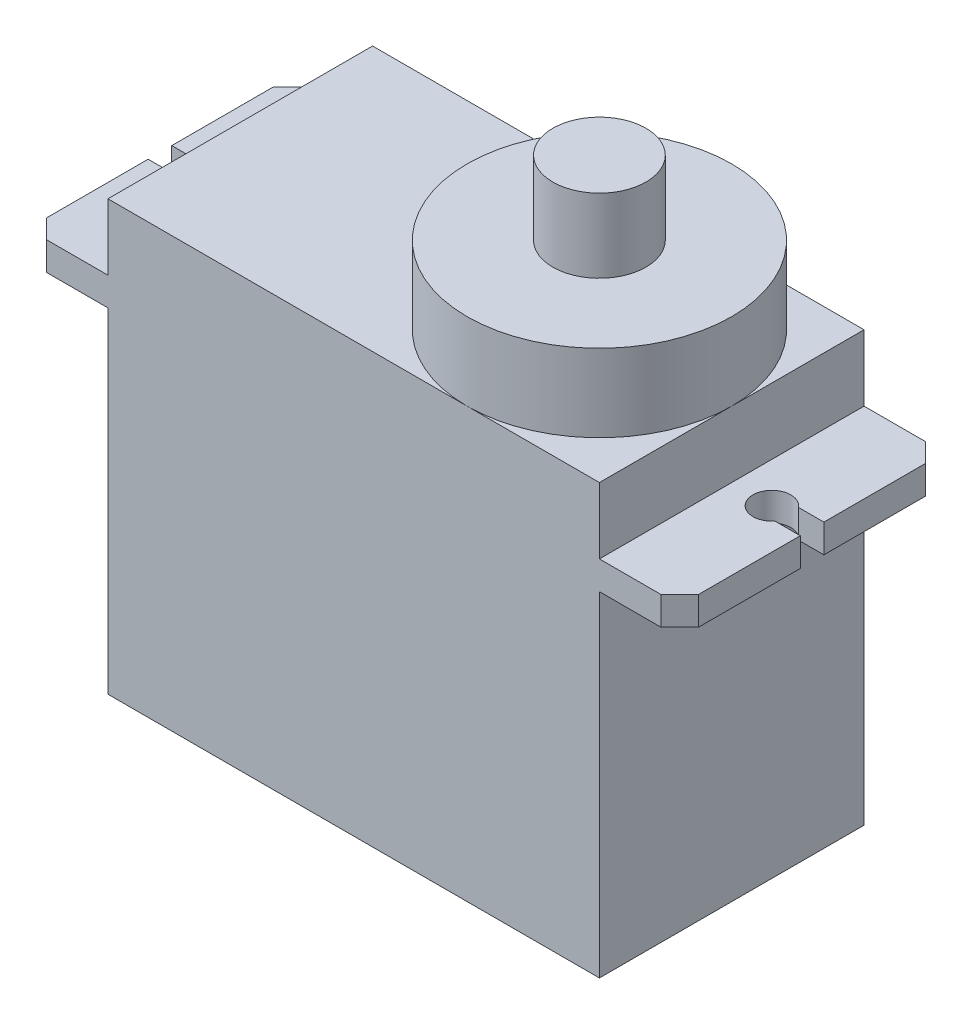
SolidWorks part; units mm, degrees
material "Custom Plastic"
ref_plane "Front Plane" through (0, 0, 0) normal (0, 0, 1) x (1, 0, 0)
ref_plane "Top Plane" through (0, 0, 0) normal (0, 1, 0) x (1, 0, 0)
ref_plane "Right Plane" through (0, 0, 0) normal (1, 0, 0) x (0, 0, -1)
sketch "Sketch1" plane through (0, 0, 0) normal (0, 1, 0) x (1, 0, 0)
  line L1 (0, 0) -> (26, 0)
  line L2 (0, 0) -> (0, 14)
  line L3 (0, 14) -> (26, 14)
  line L4 (26, 0) -> (26, 14)
  dimension "D1" = 14
  dimension "D2" = 26
extrude "Boss-Extrude1" add sketch "Sketch1" along normal blind 22.7
ref_plane "Plane1" through (0, 19.2, 0) normal (0, 1, 0) x (1, 0, 0)
sketch "Sketch2" plane through (0, 19.2, 0) normal (0, 1, 0) x (1, 0, 0)
  line L0 (26, 14) -> (0, 14) construction
  line L1 (-4.25, 14) -> (30.25, 14)
  line L2 (-4.25, 14) -> (-4.25, 0)
  line L3 (-4.25, 0) -> (30.25, 0)
  line L4 (30.25, 14) -> (30.25, 0)
  line L5 (0, 0) -> (26, 0) construction
  point P9 (13, 14)
  point P10 (13, 14)
  dimension "D1" = 34.5
extrude "Boss-Extrude2" add sketch "Sketch2" against normal blind 1.5
chamfer "Chamfer1" distance 1 angle 45 4 edges at (-4.25, 18.45, -14) (-4.25, 18.45, 0) (30.25, 18.45, -14) (30.25, 18.45, 0)
sketch "Sketch3" plane through (0, 0, 0) normal (0, -1, 0) x (1, 0, 0)
  line L0 (0, 0) -> (26, 0) construction
  line L1 (26, 0) -> (26, -14) construction
  line L2 (26, -14) -> (0, -14) construction
  circle A0 centre (19, -7) radius 7
extrude "Boss-Extrude3" add sketch "Sketch3" against normal blind 26.8
sketch "Sketch4" plane through (0, 26.8, 0) normal (0, 1, 0) x (1, 0, 0)
  circle A0 centre (19, 7) radius 2.465
  circle A1 centre (19, 7) radius 7 construction
  dimension "D1" = 4.93
extrude "Boss-Extrude4" add sketch "Sketch4" along normal blind 3.9
sketch "Sketch5" plane through (0, 19.2, 0) normal (0, 1, 0) x (1, 0, 0)
  line L0 (30.25, 1) -> (30.25, 13) construction
  line L1 (-4.25, 13) -> (-4.25, 1) construction
  circle A0 centre (28.125, 7) radius 1
  circle A1 centre (-2.125, 7) radius 1
  point P9 (30.25, 7)
  dimension "D1" = 2
  dimension "D2" = 2.125
  dimension "D3" = 2.125
extrude "Cut-Extrude1" cut sketch "Sketch5" against normal through all
sketch "Sketch7" plane through (0, 19.2, 0) normal (0, 1, 0) x (1, 0, 0)
  line L1 (28.0231, 6.375) -> (32.8405, 6.375)
  line L2 (28.0231, 6.375) -> (28.0231, 7.625)
  line L3 (28.0231, 7.625) -> (32.8405, 7.625)
  line L4 (32.8405, 6.375) -> (32.8405, 7.625)
  line L5 (28.0231, 6.375) -> (32.8405, 7.625) construction
  line L6 (28.0231, 7.625) -> (32.8405, 6.375) construction
  line L7 (-12.5678, 7.625) -> (-2.0231, 7.625)
  line L8 (-12.5678, 7.625) -> (-12.5678, 6.375)
  line L9 (-12.5678, 6.375) -> (-2.0231, 6.375)
  line L10 (-2.0231, 7.625) -> (-2.0231, 6.375)
  line L11 (-12.5678, 7.625) -> (-2.0231, 6.375) construction
  line L12 (-12.5678, 6.375) -> (-2.0231, 7.625) construction
  circle A1 centre (-2.125, 7) radius 1 construction
  point P0 (30.4318, 7)
  point P5 (-7.2955, 7)
  dimension "D1" = 1.25
  dimension "D2" = 1.25
extrude "Cut-Extrude2" cut sketch "Sketch7" against normal through all
